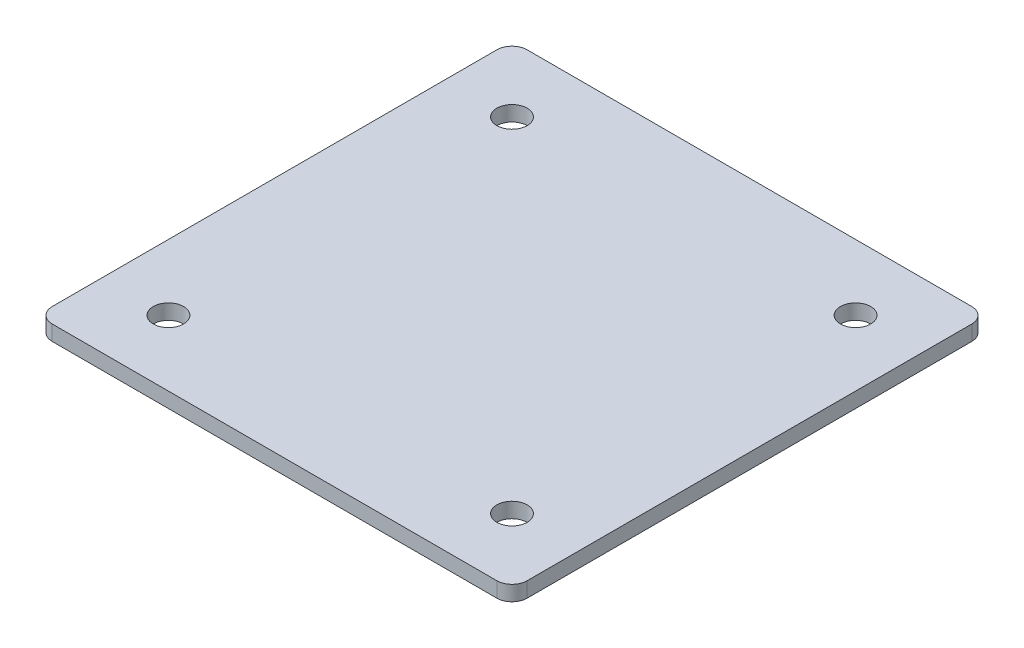
SolidWorks part; units mm, degrees
ref_plane "Спереди" through (0, 0, 0) normal (0, 0, 1) x (1, 0, 0)
ref_plane "Сверху" through (0, 0, 0) normal (0, 1, 0) x (1, 0, 0)
ref_plane "Справа" through (0, 0, 0) normal (1, 0, 0) x (0, 0, -1)
sketch "Эскиз1" plane through (0, 0, 0) normal (0, 1, 0) x (1, 0, 0)
  line L1 (-22, 23.5) -> (22, 23.5)
  line L2 (-23.5, 22) -> (-23.5, -22)
  line L3 (-22, -23.5) -> (22, -23.5)
  line L4 (23.5, 22) -> (23.5, -22)
  line L5 (-23.5, 23.5) -> (23.5, -23.5) construction
  line L6 (-23.5, -23.5) -> (23.5, 23.5) construction
  line L7 (-17, 17) -> (17, 17) construction
  line L8 (-17, 17) -> (-17, -17) construction
  line L9 (-17, -17) -> (17, -17) construction
  line L10 (17, 17) -> (17, -17) construction
  line L11 (-17, 17) -> (17, -17) construction
  line L12 (-17, -17) -> (17, 17) construction
  circle A0 centre (-17, 17) radius 1.5
  circle A1 centre (17, 17) radius 1.5
  circle A2 centre (17, -17) radius 1.5
  circle A3 centre (-17, -17) radius 1.5
  arc A4 (-23.5, -22) -> (-22, -23.5) centre (-22, -22) ccw
  arc A5 (22, -23.5) -> (23.5, -22) centre (22, -22) ccw
  arc A6 (22, 23.5) -> (23.5, 22) centre (22, 22) cw
  arc A7 (-22, 23.5) -> (-23.5, 22) centre (-22, 22) ccw
  point P0 (0, 0)
  point P6 (0, 0)
  point P27 (0, 0)
  dimension "D5" = 3
  dimension "D6" = 3
  dimension "D7" = 3
  dimension "D8" = 3
  dimension "D9" = 1.5
  dimension "D1" = 47
  dimension "D2" = 47
  dimension "D3" = 34
  dimension "D4" = 34
extrude "Бобышка-Вытянуть1" add sketch "Эскиз1" along normal blind 1.5
